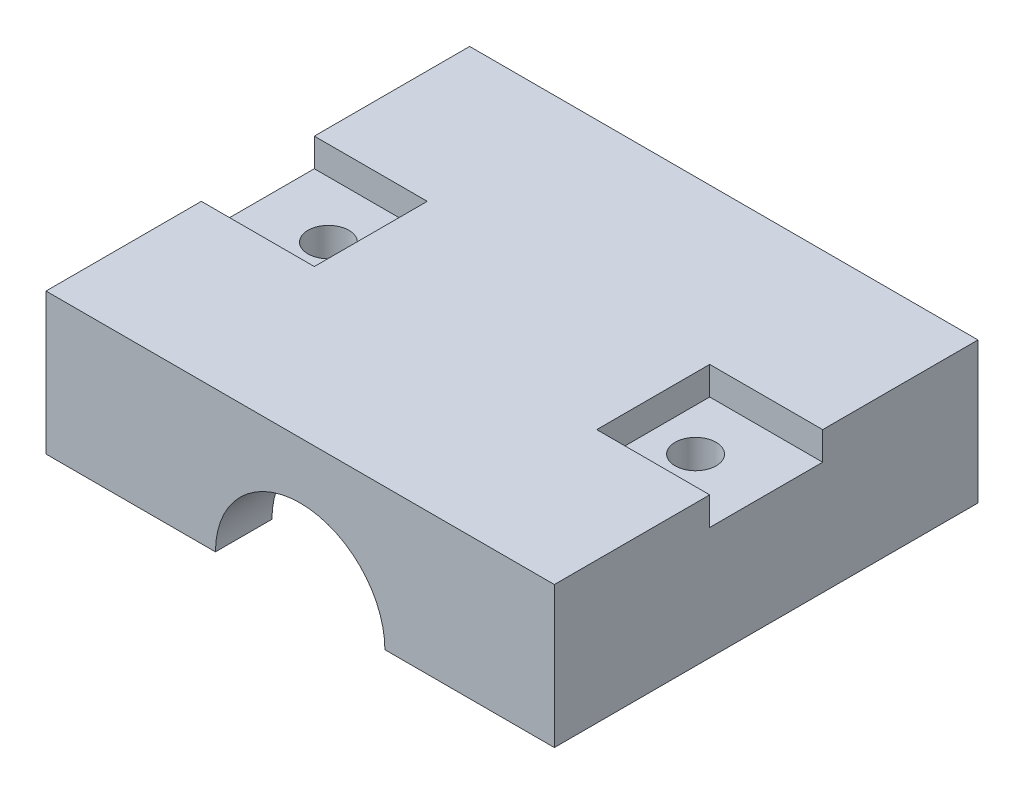
SolidWorks part; units mm, degrees
ref_plane "前视基准面" through (0, 0, 0) normal (0, 0, 1) x (1, 0, 0)
ref_plane "上视基准面" through (0, 0, 0) normal (0, 1, 0) x (1, 0, 0)
ref_plane "右视基准面" through (0, 0, 0) normal (1, 0, 0) x (0, 0, -1)
other "Configuration Table"
sketch "草图2" plane through (0, 0, 0) normal (0, 1, 0) x (1, 0, 0)
  line L1 (0, 0) -> (-36, 0)
  line L2 (0, 0) -> (0, 30)
  line L3 (0, 30) -> (-36, 30)
  line L4 (-36, 0) -> (-36, 30)
  dimension "D1" = 36
  dimension "D2" = 30
extrude "凸台-拉伸1" add sketch "草图2" along normal blind 10
sketch "草图3" plane through (0, 0, 0) normal (0, 0, 1) x (1, 0, 0)
  line L0 (-36, 0) -> (0, 0) construction
  circle A0 centre (-18, 0) radius 6
  dimension "D1" = 12
extrude "切除-拉伸1" cut sketch "草图3" against normal blind 20
sketch "草图4" plane through (0, 0, -20) normal (0, 0, 1) x (1, 0, 0)
  line L0 (-24, 0) -> (-12, 0) construction
  circle A0 centre (-18, 0) radius 8.1
  dimension "D1" = 16.2
extrude "切除-拉伸2" cut sketch "草图4" against normal blind 5.2
sketch "草图5" plane through (0, 0, 0) normal (0, -1, 0) x (1, 0, 0)
  line L0 (-36, -15) -> (-31, -15) construction
  line L1 (-36, -30) -> (-36, 0) construction
  line L2 (-18, 0) -> (-18, -4.475) construction
  line L3 (-12, 0) -> (-24, 0) construction
  circle A0 centre (-31, -15) radius 1.45
  circle A1 centre (-5, -15) radius 1.45
  dimension "D1" = 2.9
  dimension "D2" = 5
extrude "切除-拉伸3" cut sketch "草图5" against normal blind 8
sketch "草图6" plane through (0, 8, 0) normal (0, -1, 0) x (1, 0, 0)
  line L1 (-36, -11) -> (-28, -11)
  line L2 (-36, -11) -> (-36, -19)
  line L3 (-36, -19) -> (-28, -19)
  line L4 (-28, -11) -> (-28, -19)
  line L6 (-36, -30) -> (-36, 0) construction
  line L7 (-24, -20) -> (-24, 0) construction
  line L8 (-26.1, -20) -> (-9.9, -20) construction
  line L9 (-18, 0) -> (-18, -8.6033) construction
  line L10 (-12, 0) -> (-24, 0) construction
  line L11 (-8, -11) -> (-8, -19)
  line L12 (0, -19) -> (-8, -19)
  line L13 (0, -11) -> (0, -19)
  line L14 (0, -11) -> (-8, -11)
  dimension "D1" = 4
  dimension "D2" = 1
  dimension "D3" = 8
extrude "切除-拉伸4" cut sketch "草图6" against normal blind 8
sketch "草图7" plane through (0, 0, 0) normal (0, 0, 1) x (1, 0, 0)
  line L1 (-26.1, 0) -> (-9.9, 0)
  line L2 (-26.1, 0) -> (-9.9, 0)
  arc A1 (-9.9, 0) -> (-26.1, 0) centre (-18, 0) ccw
  arc A2 (-9.9, 0) -> (-26.1, 0) centre (-18, 0) ccw
  dimension "D1" = 0
extrude "切除-拉伸5" cut sketch "草图7" against normal blind 9.2
sketch "草图8" plane through (0, 0, 0) normal (0, 0, 1) x (1, 0, 0)
  line L2 (-12, 0) -> (-9.9, 0)
  line L3 (-26.1, 0) -> (-24, 0)
  line L4 (-12, 0) -> (-9.9, 0)
  line L5 (-26.1, 0) -> (-24, 0)
  arc A2 (-12, 0) -> (-24, 0) centre (-18, 0) ccw
  arc A3 (-9.9, 0) -> (-26.1, 0) centre (-18, 0) ccw
  arc A4 (-12, 0) -> (-24, 0) centre (-18, 0) ccw
  arc A5 (-9.9, 0) -> (-26.1, 0) centre (-18, 0) ccw
  dimension "D1" = 0
extrude "凸台-拉伸2" add sketch "草图8" against normal blind 4
